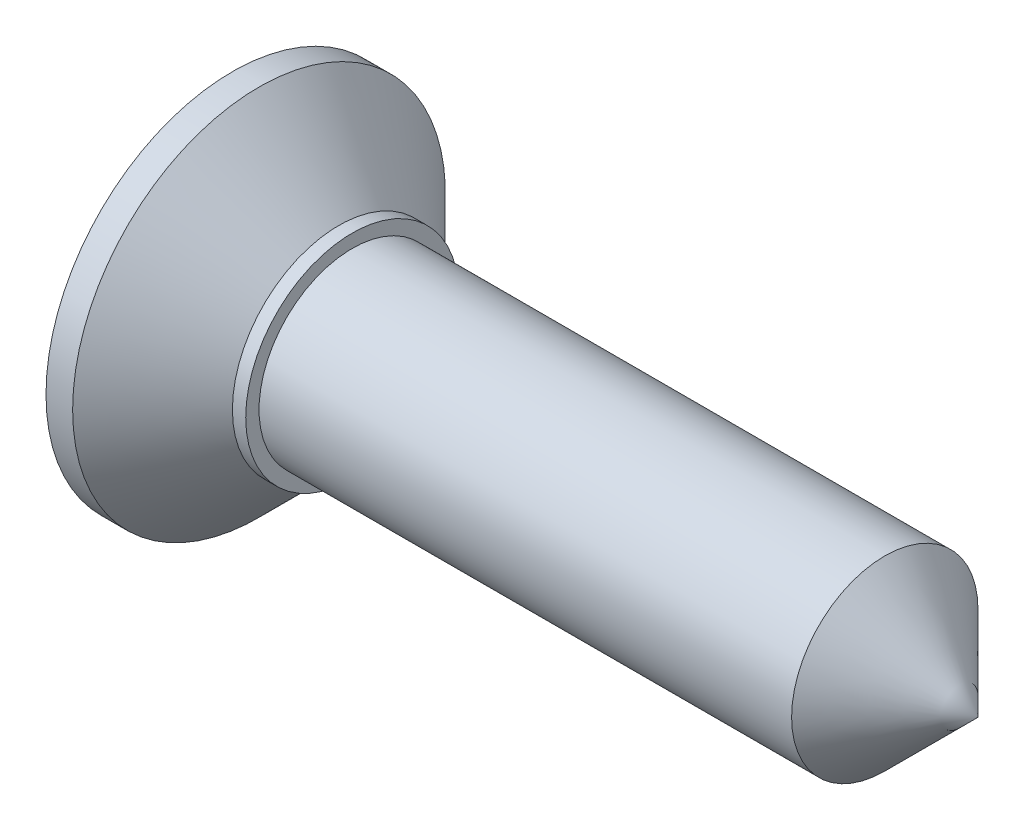
SolidWorks part; units mm, degrees
material "Plain Carbon Steel"
ref_plane "Front Plane" through (0, 0, 0) normal (0, 0, 1) x (1, 0, 0)
ref_plane "Top Plane" through (0, 0, 0) normal (0, 1, 0) x (1, 0, 0)
ref_plane "Right Plane" through (0, 0, 0) normal (1, 0, 0) x (0, 0, -1)
ref_plane "Plane1" through (0, 0, 0) normal (0, 0, -1) x (-1, 0, 0)
sketch "Sketch1" plane through (0, 0, 0) normal (0, 0, -1) x (-1, 0, 0)
  line L0 (-2.25, 2) -> (-2.25, 0)
  line L1 (-2.25, 0) -> (0, 0)
  line L2 (0, 0) -> (0, 3.5)
  line L3 (0, 3.5) -> (-0.5, 3.5)
  line L4 (-0.5, 3.5) -> (-2, 2)
  line L5 (-2, 2) -> (-2.25, 2)
  line L6 (-2.25, 0) -> (0, 0) construction
revolve "Revolve1" add sketch "Sketch1" angle 360 about L6
sketch "Sketch2" plane through (2.25, 0, 0) normal (1, 0, 0) x (0, 0, -1)
  circle A0 centre (0, 0) radius 1.75
extrude "Boss-Extrude1" add sketch "Sketch2" along normal blind 10
sketch "Sketch3" plane through (0, 0, 0) normal (0, 0, 1) x (1, 0, 0)
  line L0 (12.25, 1.75) -> (12.25, 0)
  line L1 (12.25, 0) -> (14, 0)
  line L2 (14, 0) -> (12.25, 1.75)
  line L3 (14.95, 0) -> (17.9812, 0) construction
  line L4 (12.25, -1.75) -> (12.25, 1.75) construction
  dimension "D1" = 1.75
  dimension "D2" = 1.75
revolve "Revolve2" add sketch "Sketch3" angle 360 about L3
sketch "Sketch4" plane through (0, 0, 0) normal (-1, 0, 0) x (0, 0, 1)
  line L0 (-0.6054, -0.43) -> (-0.6054, -0.6054)
  line L1 (-0.6054, -0.6054) -> (-0.43, -0.6054)
  line L2 (-0.43, -0.6054) -> (-0.43, -2.15)
  line L3 (-0.43, -2.15) -> (0.43, -2.15)
  line L4 (0.43, -2.15) -> (0.43, -0.6054)
  line L5 (0.43, -0.6054) -> (0.6054, -0.6054)
  line L6 (0.6054, -0.6054) -> (0.6054, -0.43)
  line L7 (0.6054, -0.43) -> (2.15, -0.43)
  line L8 (2.15, -0.43) -> (2.15, 0.43)
  line L9 (2.15, 0.43) -> (0.6054, 0.43)
  line L10 (0.6054, 0.43) -> (0.6054, 0.6054)
  line L11 (0.6054, 0.6054) -> (0.43, 0.6054)
  line L12 (0.43, 0.6054) -> (0.43, 2.15)
  line L13 (0.43, 2.15) -> (-0.43, 2.15)
  line L14 (-0.43, 2.15) -> (-0.43, 0.6054)
  line L15 (-0.43, 0.6054) -> (-0.6054, 0.6054)
  line L16 (-0.6054, 0.6054) -> (-0.6054, 0.43)
  line L17 (-0.6054, 0.43) -> (-2.15, 0.43)
  line L18 (-2.15, 0.43) -> (-2.15, -0.43)
  line L19 (-2.15, -0.43) -> (-0.6054, -0.43)
extrude "Cut-Extrude1" cut sketch "Sketch4" against normal blind 1
draft "Draft1" type of draft neutral plane draft angle 40 faces to draft 1 face at (0.5, -0.6054, -0.5177) neutral plane through (1, -0.6054, -0.43) neutral plane normal (0, 0, 1) reverse direction yes parameters "D1"=40
draft "Draft2" type of draft neutral plane draft angle 40 faces to draft 1 face at (0.5, -0.6054, 0.5177) neutral plane through (1, -2.15, 0.43) neutral plane normal (0, 0, -1) reverse direction yes parameters "D1"=40
draft "Draft3" type of draft neutral plane draft angle 40 faces to draft 1 face at (0.5, -0.5913, 0.6054) neutral plane through (1, -0.43, 0.6054) neutral plane normal (0, 1, 0) reverse direction yes parameters "D1"=40
draft "Draft4" type of draft neutral plane draft angle 40 faces to draft 1 face at (0.5, 0.5177, 0.6054) neutral plane through (1, 0.43, 2.15) neutral plane normal (0, -1, 0) reverse direction yes parameters "D1"=40
draft "Draft5" type of draft neutral plane draft angle 40 faces to draft 1 face at (0.5, 0.6054, 0.5913) neutral plane through (1, 0.6054, 0.43) neutral plane normal (0, 0, -1) reverse direction yes parameters "D1"=40
draft "Draft6" type of draft neutral plane draft angle 40 faces to draft 1 face at (0.5, 0.6054, -0.5177) neutral plane through (1, 2.15, -0.43) neutral plane normal (0, 0, 1) reverse direction yes parameters "D1"=40
draft "Draft7" type of draft neutral plane draft angle 40 faces to draft 1 face at (0.5, 0.5913, -0.6054) neutral plane through (1, 0.43, -0.6054) neutral plane normal (0, -1, 0) reverse direction yes parameters "D1"=40
draft "Draft8" type of draft neutral plane draft angle 40 faces to draft 1 face at (0.5, -0.5913, -0.6054) neutral plane through (1, -0.43, -2.15) neutral plane normal (0, 1, 0) reverse direction yes parameters "D1"=40
